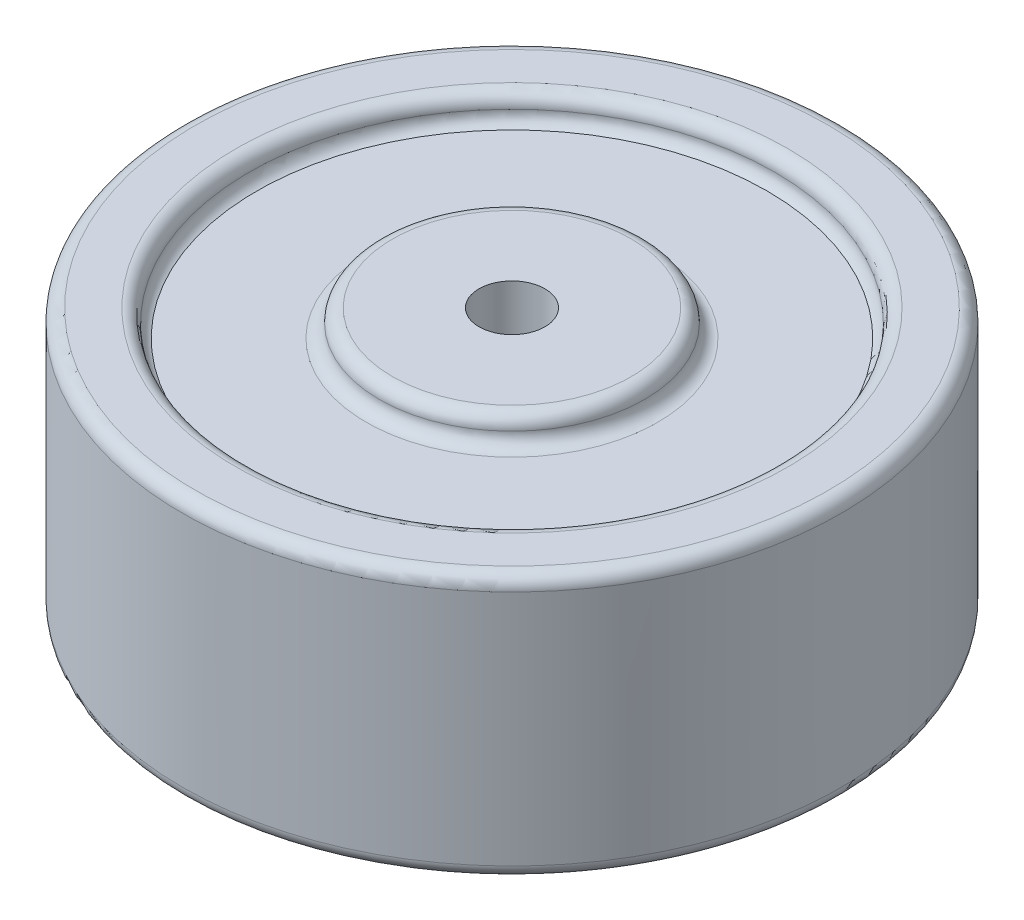
SolidWorks part; units mm, degrees
material "Natural Rubber"
ref_plane "Front Plane" through (0, 0, 0) normal (0, 0, 1) x (1, 0, 0)
ref_plane "Top Plane" through (0, 0, 0) normal (0, 1, 0) x (1, 0, 0)
ref_plane "Right Plane" through (0, 0, 0) normal (1, 0, 0) x (0, 0, -1)
sketch "Sketch1" plane through (0, 0, 0) normal (0, 0, 1) x (1, 0, 0)
  line L0 (0, 0) -> (-9.0559, 0)
  line L1 (-20.9279, 0) -> (-25, 0)
  line L2 (-19.3546, -2) -> (-11.0559, -2)
  line L3 (0, 0) -> (0, 8.6716) construction
  line L4 (0, 0) -> (0, -3.6937) construction
  line L5 (0, -10) -> (-9.0559, -10) construction
  line L6 (-19.3546, -18) -> (-11.0559, -18)
  line L7 (-20.9279, -20) -> (-25, -20)
  line L8 (0, -20) -> (-9.0559, -20)
  line L9 (-25, 0) -> (-25, -20)
  line L10 (0, -20) -> (0, 0)
  arc A0 (-19.929, -1.0473) -> (-19.3546, -2) centre (-18.9301, -1.0946) ccw
  arc A1 (-9.0559, 0) -> (-10.0559, -1) centre (-9.0559, -1) ccw
  arc A2 (-20.9279, 0) -> (-19.929, -1.0473) centre (-20.9279, -1) cw
  arc A3 (-11.0559, -2) -> (-10.0559, -1) centre (-11.0559, -1) ccw
  arc A4 (-11.0559, -18) -> (-10.0559, -19) centre (-11.0559, -19) cw
  arc A5 (-20.9279, -20) -> (-19.929, -18.9527) centre (-20.9279, -19) ccw
  arc A6 (-9.0559, -20) -> (-10.0559, -19) centre (-9.0559, -19) cw
  arc A7 (-19.929, -18.9527) -> (-19.3546, -18) centre (-18.9301, -18.9054) cw
  point P8 (-10, 0)
  point P11 (-20, 0)
  point P31 (-20, -20)
  point P32 (-10, -20)
  dimension "D4" = 1
  dimension "D5" = 2
  dimension "D6" = 1
  dimension "D7" = 1
  dimension "D8" = 10
  dimension "D1" = 5
  dimension "D2" = 10
  dimension "D3" = 10
revolve "Revolve1" add sketch "Sketch1" angle 360 about L3
sketch "Sketch3" plane through (0, -20, 0) normal (0, -1, 0) x (1, 0, 0)
  circle A0 centre (0, 0) radius 2.5
  dimension "D1" = 5
extrude "Cut-Extrude2" cut sketch "Sketch3" against normal up to surface (20 mm away) up to face at (0, 0, -9.0559)
fillet "Fillet2" radius 1 2 edges at (0, 0, -25) (0, -20, -25)
